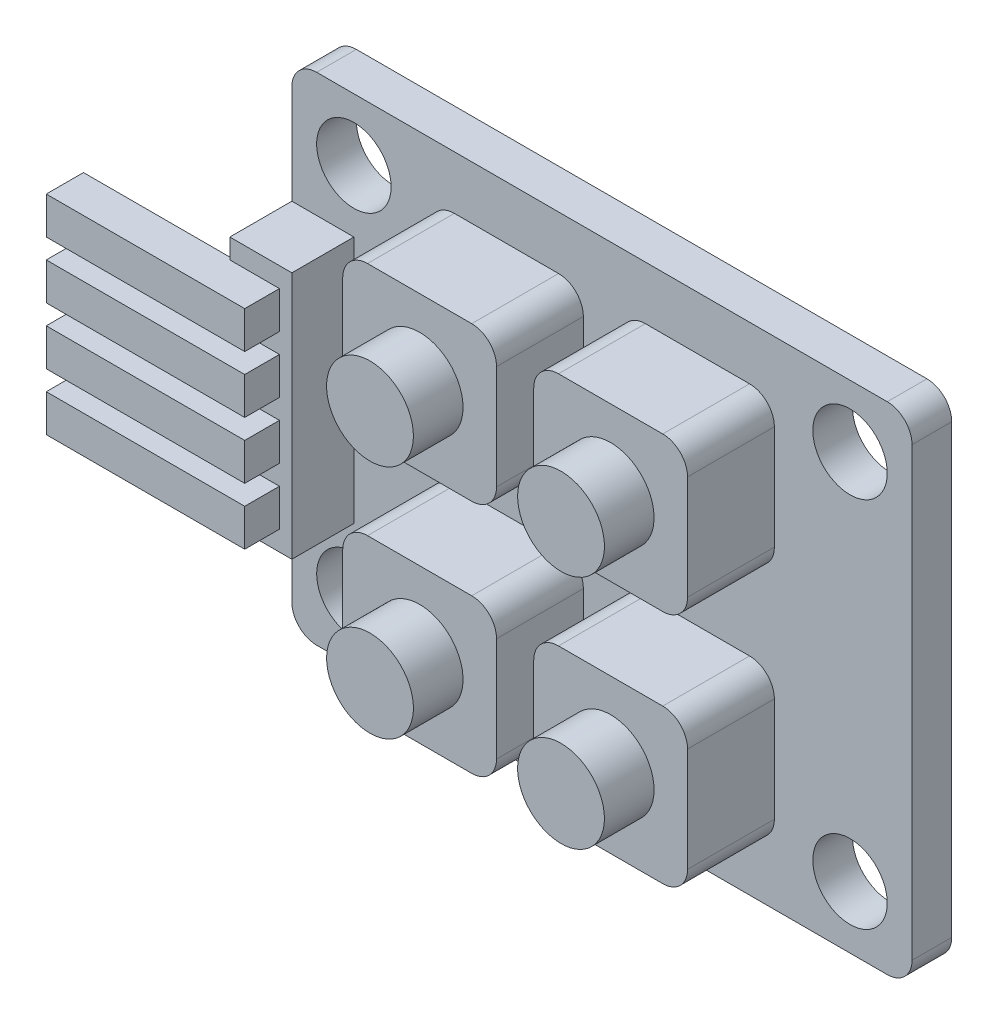
SolidWorks part; units mm, degrees
ref_plane "Front Plane" through (0, 0, 0) normal (0, 0, 1) x (1, 0, 0)
ref_plane "Top Plane" through (0, 0, 0) normal (0, 1, 0) x (1, 0, 0)
ref_plane "Right Plane" through (0, 0, 0) normal (1, 0, 0) x (0, 0, -1)
sketch "Sketch1" plane through (0, 0, 0) normal (0, 0, 1) x (1, 0, 0)
  line L1 (-12.5, -10) -> (12.5, -10)
  line L2 (-12.5, -10) -> (-12.5, 10)
  line L3 (-12.5, 10) -> (12.5, 10)
  line L4 (12.5, -10) -> (12.5, 10)
  line L5 (-12.5, -10) -> (12.5, 10) construction
  line L6 (-12.5, 10) -> (12.5, -10) construction
  point P0 (0, 0)
  dimension "D1" = 25
  dimension "D2" = 20
extrude "Boss-Extrude1" add sketch "Sketch1" along normal blind 1.6
sketch "Sketch2" plane through (0, 0, 1.6) normal (0, 0, 1) x (1, 0, 0)
  line L0 (-3.85, 10) -> (-3.85, -10) construction
  line L1 (12.5, 10) -> (-12.5, 10) construction
  line L2 (-12.5, -10) -> (12.5, -10) construction
  line L3 (6.15, 10) -> (6.15, -10) construction
  line L4 (-12.5, 4.75) -> (12.5, 4.75) construction
  line L5 (-12.5, 10) -> (-12.5, -10) construction
  line L6 (12.5, -10) -> (12.5, 10) construction
  line L8 (0, 10) -> (0, -10) construction
  line L9 (-12.5, 0) -> (12.5, 0) construction
  line L10 (6.95, 7.85) -> (0.75, 7.85)
  line L11 (-6.95, 1.65) -> (-0.75, 1.65)
  line L12 (-6.95, 1.65) -> (-6.95, 7.85)
  line L13 (-6.95, 7.85) -> (-0.75, 7.85)
  line L14 (-0.75, 1.65) -> (-0.75, 7.85)
  line L15 (-6.95, 1.65) -> (-0.75, 7.85) construction
  line L16 (-6.95, 7.85) -> (-0.75, 1.65) construction
  line L17 (0.75, 1.65) -> (0.75, 7.85)
  line L18 (6.95, 1.65) -> (0.75, 1.65)
  line L19 (6.95, 1.65) -> (6.95, 7.85)
  line L20 (6.95, -1.65) -> (6.95, -7.85)
  line L21 (6.95, -1.65) -> (0.75, -1.65)
  line L22 (0.75, -1.65) -> (0.75, -7.85)
  line L23 (6.95, -7.85) -> (0.75, -7.85)
  line L24 (-6.95, -7.85) -> (-0.75, -7.85)
  line L25 (-0.75, -1.65) -> (-0.75, -7.85)
  line L26 (-6.95, -1.65) -> (-0.75, -1.65)
  line L27 (-6.95, -1.65) -> (-6.95, -7.85)
  point P20 (-3.85, 4.75)
  dimension "D1" = 3.3
  dimension "D2" = 10
  dimension "D3" = 1.5
  dimension "D5" = 6.2
  dimension "D6" = 6.2
extrude "Boss-Extrude2" add sketch "Sketch2" along normal blind 3.5
sketch "Sketch3" plane through (0, 0, 5.1) normal (0, 0, 1) x (1, 0, 0)
  line L0 (0, 10) -> (0, -10) construction
  line L1 (12.5, 10) -> (-12.5, 10) construction
  line L2 (-12.5, -10) -> (12.5, -10) construction
  line L3 (-12.5, 0) -> (12.5, 0) construction
  line L4 (-12.5, 10) -> (-12.5, -10) construction
  line L5 (12.5, -10) -> (12.5, 10) construction
  line L6 (-3.85, 7.85) -> (-3.85, 1.65) construction
  line L7 (-0.75, 7.85) -> (-6.95, 7.85) construction
  line L8 (-6.95, 1.65) -> (-0.75, 1.65) construction
  line L9 (-6.95, 4.75) -> (-0.75, 4.75) construction
  line L10 (-6.95, 7.85) -> (-6.95, 1.65) construction
  line L11 (-0.75, 1.65) -> (-0.75, 7.85) construction
  circle A0 centre (-3.85, 4.75) radius 1.75
  circle A1 centre (3.85, 4.75) radius 1.75
  circle A2 centre (3.85, -4.75) radius 1.75
  circle A3 centre (-3.85, -4.75) radius 1.75
  point P32 (-19.1816, 5.4463)
  point P33 (-3.85, 4.75)
  point P34 (3.85, 4.75)
  point P35 (-3.85, -4.75)
  point P36 (3.85, -4.75)
  point P37 (19.673, 9.6498)
  dimension "D1" = 3.5
extrude "Boss-Extrude3" add sketch "Sketch3" along normal blind 2
sketch "Sketch4" plane through (0, 0, 1.6) normal (0, 0, 1) x (1, 0, 0)
  line L0 (0, 10) -> (0, -10) construction
  line L1 (12.5, 10) -> (-12.5, 10) construction
  line L2 (-12.5, -10) -> (12.5, -10) construction
  line L3 (-12.5, 0) -> (12.5, 0) construction
  line L4 (-12.5, 10) -> (-12.5, -10) construction
  line L5 (12.5, -10) -> (12.5, 10) construction
  circle A0 centre (-10, 7.5) radius 1.5
  circle A1 centre (10, 7.5) radius 1.5
  circle A2 centre (10, -7.5) radius 1.5
  circle A3 centre (-10, -7.5) radius 1.5
  dimension "D1" = 3
  dimension "D2" = 2.5
  dimension "D3" = 2.5
extrude "Cut-Extrude1" cut sketch "Sketch4" against normal through all
sketch "Sketch5" plane through (0, 0, 1.6) normal (0, 0, 1) x (1, 0, 0)
  line L0 (-12.5, 10) -> (-12.5, -10) construction
  line L1 (-12.5, 5) -> (-10, 5)
  line L2 (-12.5, 5) -> (-12.5, -5)
  line L3 (-12.5, -5) -> (-10, -5)
  line L4 (-10, 5) -> (-10, -5)
  line L5 (0, 0) -> (-12.5, 0) construction
  line L6 (-10, 0) -> (-12.5, 0) construction
  dimension "D1" = 10
  dimension "D2" = 2.5
extrude "Boss-Extrude4" add sketch "Sketch5" along normal blind 2.5
sketch "Sketch6" plane through (0, 0, 4.1) normal (0, 0, 1) x (1, 0, 0)
  line L0 (-12.5, -5) -> (-10, -5) construction
  line L1 (-12, -2.7) -> (-10.5, -2.7)
  line L2 (-12, -2.7) -> (-12, -4.2)
  line L3 (-12, -4.2) -> (-10.5, -4.2)
  line L4 (-10.5, -2.7) -> (-10.5, -4.2)
  line L5 (-12.5, 5) -> (-12.5, -5) construction
  line L6 (-12, -0.4) -> (-12, -1.9)
  line L7 (-12, -0.4) -> (-10.5, -0.4)
  line L8 (-10.5, -0.4) -> (-10.5, -1.9)
  line L9 (-12, -1.9) -> (-10.5, -1.9)
  line L10 (-12, 1.9) -> (-12, 0.4)
  line L11 (-12, 1.9) -> (-10.5, 1.9)
  line L12 (-10.5, 1.9) -> (-10.5, 0.4)
  line L13 (-12, 0.4) -> (-10.5, 0.4)
  line L14 (-12, 4.2) -> (-12, 2.7)
  line L15 (-12, 4.2) -> (-10.5, 4.2)
  line L16 (-10.5, 4.2) -> (-10.5, 2.7)
  line L17 (-12, 2.7) -> (-10.5, 2.7)
  point P8 (-11.25, -1.9)
  dimension "D1" = 1.5
  dimension "D2" = 1.5
  dimension "D3" = 0.8
  dimension "D4" = 0.5
  dimension "D6" = 0.8
  dimension "D5" = 4
extrude "Boss-Extrude5" add sketch "Sketch6" along normal blind 1.4
sketch "Sketch7" plane through (-12, 0, 0) normal (-1, 0, 0) x (0, 0, 1)
  line L0 (5.5, -4.2) -> (4.1, -4.2) construction
  line L1 (5.5, -2.7) -> (4, -2.7)
  line L2 (5.5, -2.7) -> (5.5, -4.2)
  line L3 (5.5, -4.2) -> (4, -4.2)
  line L4 (4, -2.7) -> (4, -4.2)
  line L5 (5.5, -1.9) -> (4.1, -1.9) construction
  line L6 (5.5, -0.4) -> (4, -0.4)
  line L7 (5.5, -0.4) -> (5.5, -1.9)
  line L8 (5.5, -1.9) -> (4, -1.9)
  line L9 (4, -0.4) -> (4, -1.9)
  line L10 (5.5, 0.4) -> (4.1, 0.4) construction
  line L11 (5.5, 1.9) -> (4, 1.9)
  line L12 (5.5, 1.9) -> (5.5, 0.4)
  line L13 (5.5, 0.4) -> (4, 0.4)
  line L14 (4, 1.9) -> (4, 0.4)
  line L15 (5.5, 2.7) -> (4.1, 2.7) construction
  line L16 (5.5, 4.2) -> (4, 4.2)
  line L17 (5.5, 4.2) -> (5.5, 2.7)
  line L18 (5.5, 2.7) -> (4, 2.7)
  line L19 (4, 4.2) -> (4, 2.7)
  dimension "D1" = 1.5
  dimension "D2" = 1.5
  dimension "D3" = 1.5
  dimension "D4" = 1.5
extrude "Boss-Extrude6" add sketch "Sketch7" along normal blind 6.5
fillet "Fillet1" radius 1 20 edges at (-12.5, -10, 0.8) (12.5, -10, 0.8) (-12.5, 10, 0.8) (12.5, 10, 0.8) (-6.95, 1.65, 3.35) (-0.75, 1.65, 3.35) (-6.95, 7.85, 3.35) (-0.75, 7.85, 3.35) (-6.95, -7.85, 3.35) (-6.95, -1.65, 3.35) (-0.75, -1.65, 3.35) (-0.75, -7.85, 3.35) (0.75, -7.85, 3.35) (6.95, -7.85, 3.35) (6.95, -1.65, 3.35) (0.75, -1.65, 3.35) (0.75, 1.65, 3.35) (0.75, 7.85, 3.35) (6.95, 1.65, 3.35) (6.95, 7.85, 3.35)
sketch "Sketch9" plane through (0, 0, 7.1) normal (0, 0, 1) x (1, 0, 0)
  line L0 (-3.85, 4.75) -> (3.85, -4.75)
  line L1 (-6.95, 1.65) -> (-0.75, 7.85) construction
sketch "Sketch10" plane through (0, 0, 0) normal (0, 0, -1) x (-1, 0, 0)
  line L0 (3.85, 4.75) -> (-3.85, -4.75)
  point P4 (0, 0)
